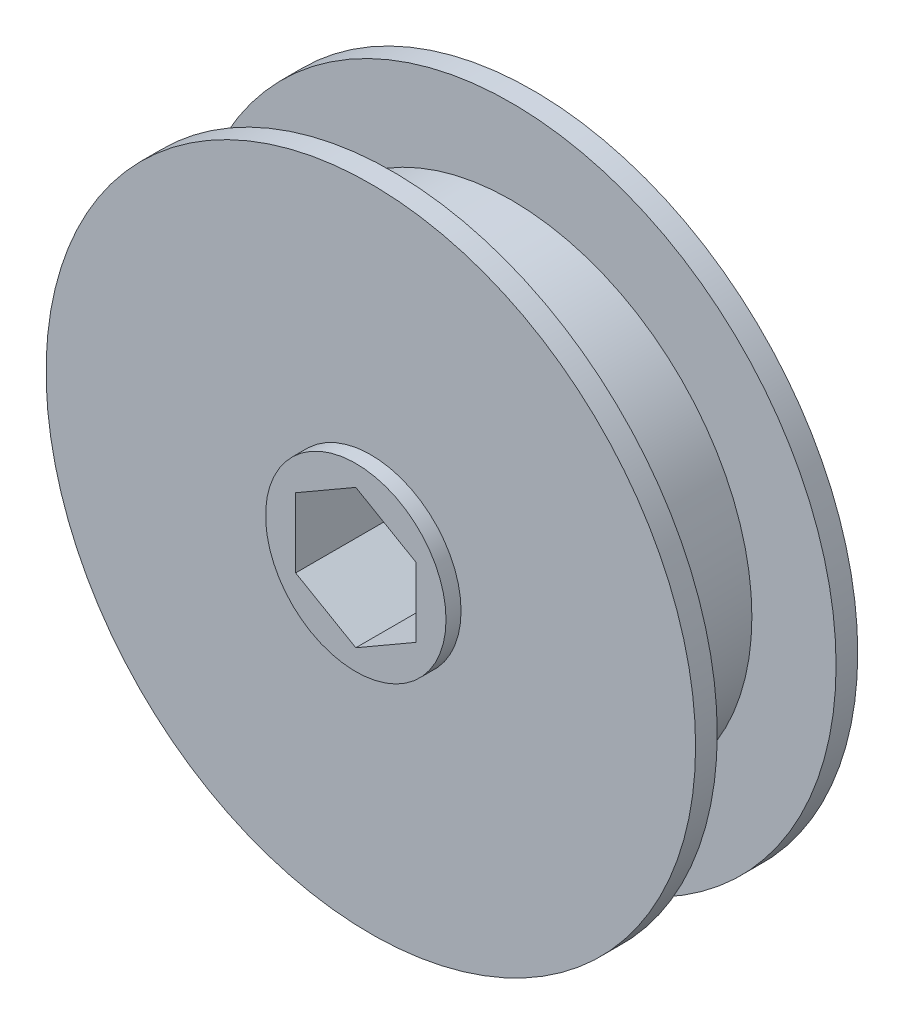
SolidWorks part; units mm, degrees
ref_plane "Front Plane" through (0, 0, 0) normal (0, 0, 1) x (1, 0, 0)
ref_plane "Top Plane" through (0, 0, 0) normal (0, 1, 0) x (1, 0, 0)
ref_plane "Right Plane" through (0, 0, 0) normal (1, 0, 0) x (0, 0, -1)
sketch "Sketch2" plane through (0, 0, 0) normal (0, 0, 1) x (1, 0, 0)
  line L1 (0, 7.3323) -> (-6.35, 3.6662)
  line L2 (-6.35, 3.6662) -> (-6.35, -3.6662)
  line L3 (-6.35, -3.6662) -> (0, -7.3323)
  line L4 (0, -7.3323) -> (6.35, -3.6662)
  line L5 (6.35, -3.6662) -> (6.35, 3.6662)
  line L6 (6.35, 3.6662) -> (0, 7.3323)
  circle A0 centre (0, 0) radius 25.4
  circle A1 centre (0, 0) radius 6.35 construction
  point P3 (0, 0)
  dimension "D1" = 50.8
  dimension "D2" = 12.7
extrude "Boss-Extrude3" add sketch "Sketch2" along normal mid plane 16.4211
sketch "Sketch3" plane through (0, 0, 8.2105) normal (0, 0, 1) x (1, 0, 0)
  line L1 (0, 7.3323) -> (-6.35, 3.6662)
  line L2 (-6.35, 3.6662) -> (-6.35, -3.6662)
  line L3 (-6.35, -3.6662) -> (0, -7.3323)
  line L4 (0, -7.3323) -> (6.35, -3.6662)
  line L5 (6.35, -3.6662) -> (6.35, 3.6662)
  line L6 (6.35, 3.6662) -> (0, 7.3323)
  circle A0 centre (0, 0) radius 34.29
  circle A1 centre (0, 0) radius 6.35 construction
  point P3 (0, 0)
  dimension "D1" = 12.7
  dimension "D2" = 68.58
extrude "Boss-Extrude4" add sketch "Sketch3" along normal mid plane 3.8735
sketch "Sketch4" plane through (0, 0, 10.1473) normal (0, 0, 1) x (1, 0, 0)
  circle A0 centre (0, 0) radius 9.525
  circle A1 centre (0, 0) radius 34.29
  circle A2 centre (0, 0) radius 34.29 construction
  dimension "D1" = 19.05
extrude "Cut-Extrude1" cut sketch "Sketch4" against normal blind 1.5875
mirror "Mirror1" about plane through (0, 0, 0) normal (0, 0, 1) of "Cut-Extrude1", "Boss-Extrude4"
